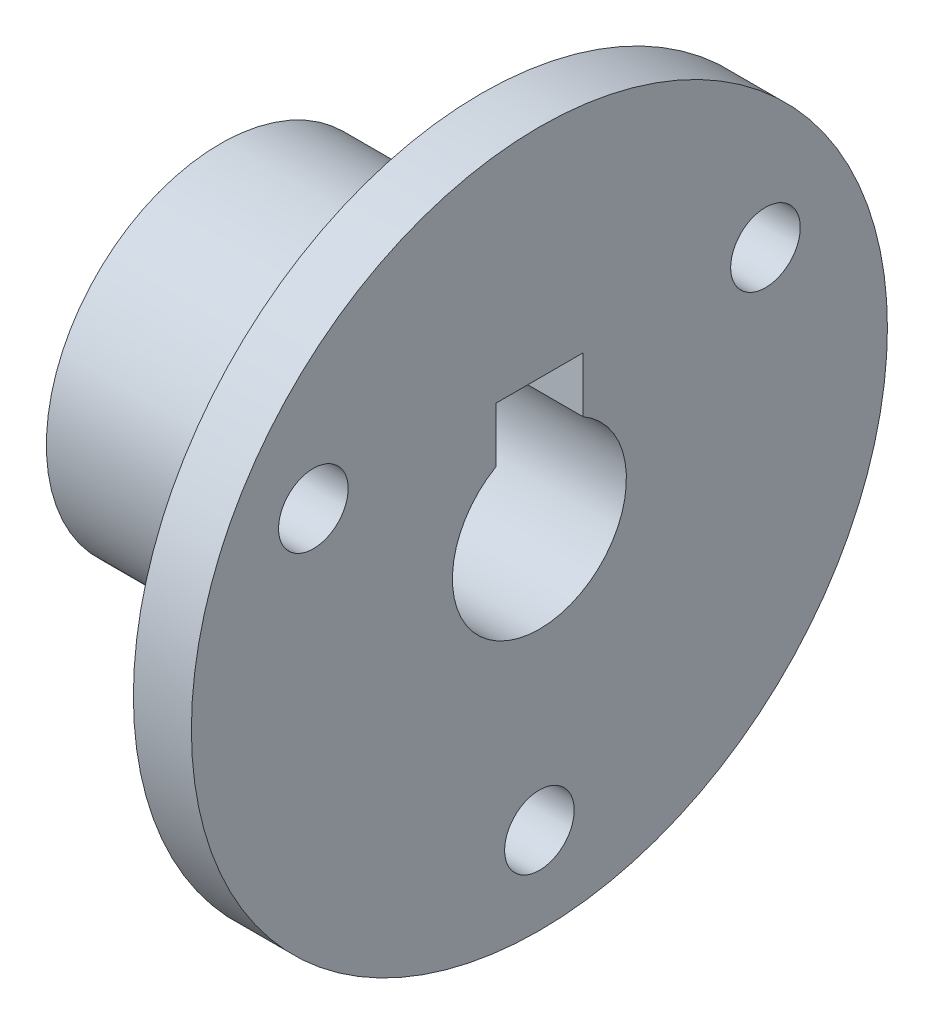
SolidWorks part; units mm, degrees
ref_plane "Front Plane" through (0, 0, 0) normal (0, 0, 1) x (1, 0, 0)
ref_plane "Top Plane" through (0, 0, 0) normal (0, 1, 0) x (1, 0, 0)
ref_plane "Right Plane" through (0, 0, 0) normal (1, 0, 0) x (0, 0, -1)
ref_plane "Plane1" through (0, 0, 0) normal (0, 0, -1) x (-1, 0, 0)
sketch "Sketch1" plane through (0, 0, 0) normal (0, 0, -1) x (-1, 0, 0)
  line L0 (-10, 60) -> (-10, 0)
  line L1 (-10, 0) -> (0, 0)
  line L2 (0, 0) -> (0, 60)
  line L3 (0, 60) -> (-10, 60)
  line L4 (-10, 0) -> (0, 0) construction
revolve "Revolve1" add sketch "Sketch1" angle 360 about L4
sketch "Sketch2" plane through (0, 0, 0) normal (-1, 0, 0) x (0, 0, 1)
  circle A0 centre (0, 0) radius 30
extrude "Boss-Extrude1" add sketch "Sketch2" along normal blind 45
sketch "Sketch3" plane through (-45, 0, 0) normal (-1, 0, 0) x (0, 0, 1)
  line L0 (-7.5, 22.4956) -> (-7.5, 12.9904)
  line L1 (7.5, 12.9904) -> (7.5, 22.4956)
  line L2 (7.5, 22.4956) -> (-7.5, 22.4956)
  arc A0 (-7.5, 12.9904) -> (7.5, 12.9904) centre (0, 0) cw
extrude "Cut-Extrude1" cut sketch "Sketch3" against normal through all
sketch "Sketch4" plane through (0, 0, 0) normal (0, 0, -1) x (-1, 0, 0)
  line L0 (-10, 15) -> (-10, 0)
  line L1 (-10, 0) -> (45, 0)
  line L2 (45, 0) -> (45, 15)
  line L3 (45, 15) -> (-10, 15)
  line L4 (-10, 0) -> (45, 0) construction
revolve "Cut-Revolve1" cut sketch "Sketch4" angle 360 about L4
hole_wizard "Ø12.0 (12) Diameter Hole1" positions "Sketch6" profile "Sketch5" hole size "Ø12.0" standard "ANSI Metric"
sketch "Sketch6" plane through (0, 0, 0) normal (-1, 0, 0) x (0, 0, 1)
  point P0 (-38.9711, 22.5)
  point P1 (38.9711, 22.5)
  point P2 (0, -45)
sketch "Sketch5" plane through (0, 22.5, -38.9711) normal (0, 1, 0) x (0, 0, 1)
  line L0 (0, 0) -> (0, 10)
  line L1 (0, 10) -> (6, 10)
  line L2 (6, 10) -> (6, 0)
  line L5 (6, 0) -> (0, 0)
  line L11 (0, -6.35) -> (0, 107.95) construction
  dimension "Thru Hole Dia." = 12
  dimension "Thru Hole Depth" = 10
ref_plane "Plane2" through (-45, 12.9904, -7.5) normal (0, -1, 0) x (-1, 0, 0)
